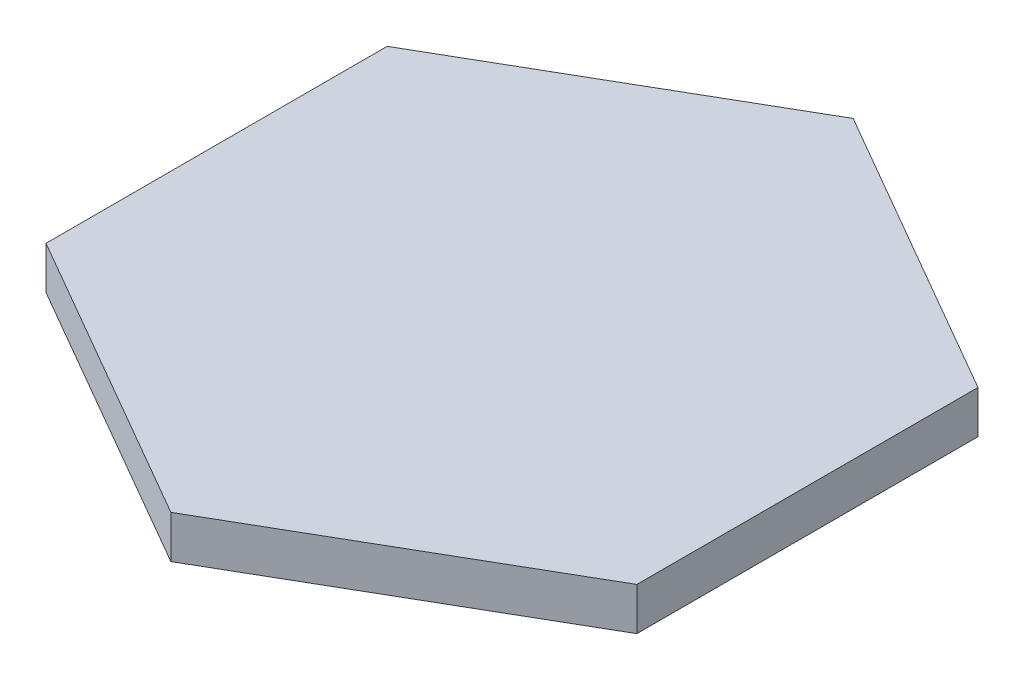
SolidWorks part; units mm, degrees
ref_plane "Front Plane" through (0, 0, 0) normal (0, 0, 1) x (1, 0, 0)
ref_plane "Top Plane" through (0, 0, 0) normal (0, 1, 0) x (1, 0, 0)
ref_plane "Right Plane" through (0, 0, 0) normal (1, 0, 0) x (0, 0, -1)
sketch "Sketch1" plane through (0, 0, 0) normal (0, 1, 0) x (1, 0, 0)
  line L1 (43.9941, 25.4) -> (0, 50.8)
  line L2 (0, 50.8) -> (-43.9941, 25.4)
  line L3 (-43.9941, 25.4) -> (-43.9941, -25.4)
  line L4 (-43.9941, -25.4) -> (0, -50.8)
  line L5 (0, -50.8) -> (43.9941, -25.4)
  line L6 (43.9941, -25.4) -> (43.9941, 25.4)
  circle A0 centre (0, 0) radius 43.9941 construction
  dimension "D1" = 50.8
  dimension "D2" = 101.6
extrude "Boss-Extrude1" add sketch "Sketch1" against normal blind 6.35
